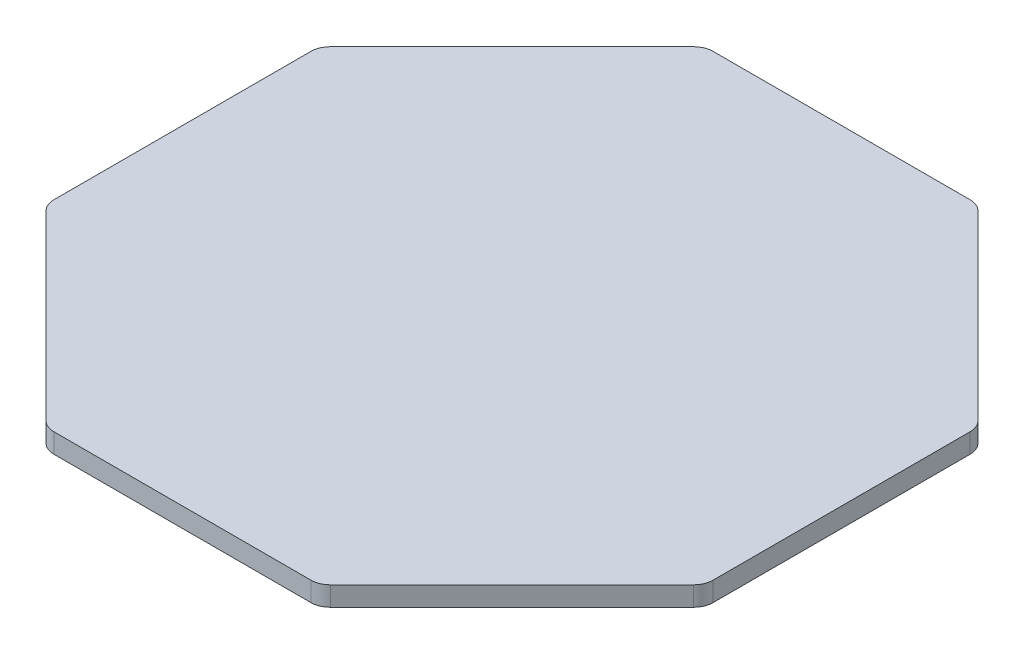
SolidWorks part; units mm, degrees
ref_plane "Front Plane" through (0, 0, 0) normal (0, 0, 1) x (1, 0, 0)
ref_plane "Top Plane" through (0, 0, 0) normal (0, 1, 0) x (1, 0, 0)
ref_plane "Right Plane" through (0, 0, 0) normal (1, 0, 0) x (0, 0, -1)
sketch "Sketch1" plane through (0, 0, 0) normal (0, 1, 0) x (1, 0, 0)
  line L0 (-14, 33.799) -> (14, 33.799)
  line L1 (14, 33.799) -> (33.799, 14)
  line L2 (33.799, 14) -> (33.799, -14)
  line L3 (33.799, -14) -> (14, -33.799)
  line L4 (14, -33.799) -> (-14, -33.799)
  line L5 (-14, -33.799) -> (-33.799, -14)
  line L6 (-33.799, -14) -> (-33.799, 14)
  line L7 (-33.799, 14) -> (-14, 33.799)
  line L8 (0, 33.799) -> (0, -33.799) construction
  point P10 (0, 0)
  dimension "D1" = 28
  dimension "D2" = 45
  dimension "D3" = 45
  dimension "D4" = 67.598
extrude "Boss-Extrude1" add sketch "Sketch1" along normal blind 2
fillet "Fillet1" radius 2 8 edges at (-33.799, 1, 14) (-33.799, 1, -14) (-14, 1, -33.799) (14, 1, -33.799) (33.799, 1, -14) (33.799, 1, 14) (14, 1, 33.799) (-14, 1, 33.799)
